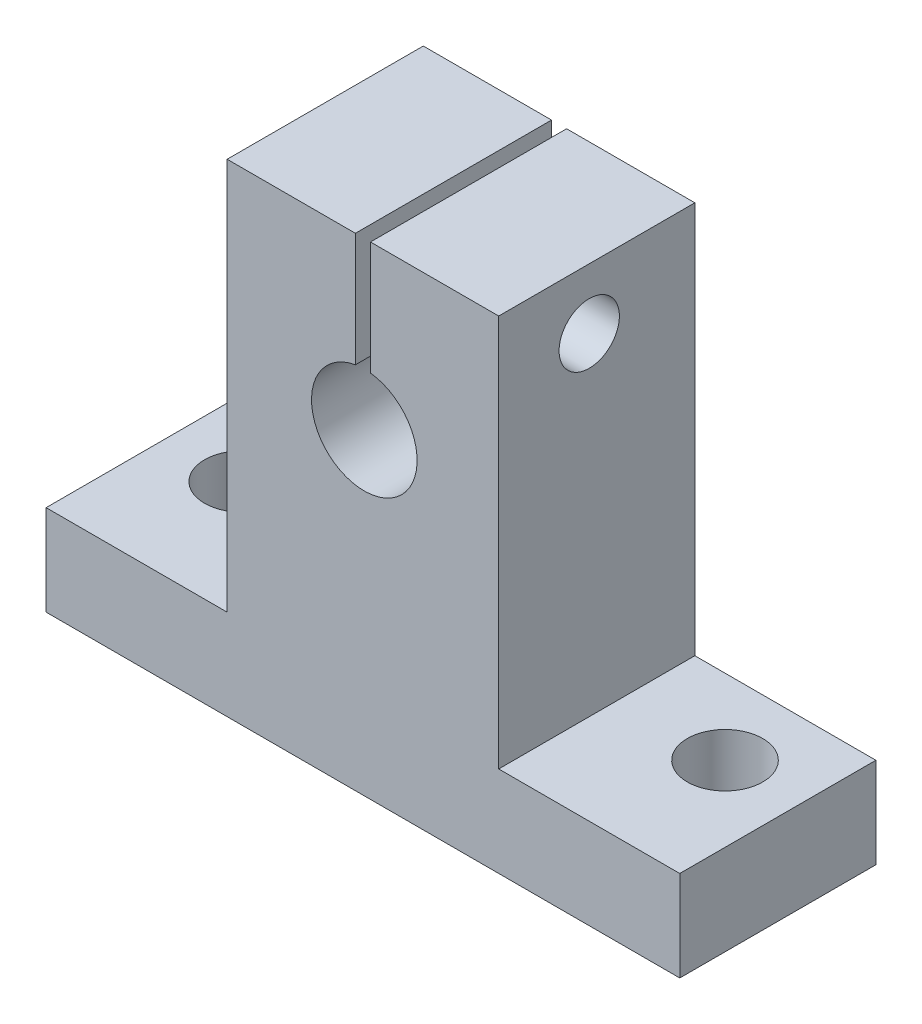
SolidWorks part; units mm, degrees
ref_plane "Front Plane" through (0, 0, 0) normal (0, 0, 1) x (1, 0, 0)
ref_plane "Top Plane" through (0, 0, 0) normal (0, 1, 0) x (1, 0, 0)
ref_plane "Right Plane" through (0, 0, 0) normal (1, 0, 0) x (0, 0, -1)
sketch "Sketch1" plane through (0, 0, 0) normal (0, 1, 0) x (1, 0, 0)
  line L1 (21, 6.5) -> (-21, 6.5)
  line L2 (21, 6.5) -> (21, -6.5)
  line L3 (21, -6.5) -> (-21, -6.5)
  line L4 (-21, 6.5) -> (-21, -6.5)
  line L5 (21, 6.5) -> (-21, -6.5) construction
  line L6 (21, -6.5) -> (-21, 6.5) construction
  circle A0 centre (-16, 1.5) radius 2.5
  circle A1 centre (16, 1.5) radius 2.5
  point P0 (0, 0)
  dimension "D4" = 5
  dimension "D8" = 5
  dimension "D1" = 13
  dimension "D2" = 42
  dimension "D3" = 5
  dimension "D5" = 5
  dimension "D6" = 5
  dimension "D7" = 5
extrude "Boss-Extrude1" add sketch "Sketch1" along normal blind 6
sketch "Sketch2" plane through (0, 6, 0) normal (0, 1, 0) x (1, 0, 0)
  line L0 (-21, -6.5) -> (21, -6.5) construction
  line L1 (-9, 6.5) -> (9, 6.5)
  line L2 (-9, 6.5) -> (-9, -6.5)
  line L3 (-9, -6.5) -> (9, -6.5)
  line L4 (9, 6.5) -> (9, -6.5)
  line L5 (-9, 6.5) -> (9, -6.5) construction
  line L6 (-9, -6.5) -> (9, 6.5) construction
  point P0 (0, 0)
  dimension "D1" = 18
extrude "Boss-Extrude2" add sketch "Sketch2" along normal blind 26
sketch "Sketch3" plane through (0, 0, 6.5) normal (0, 0, 1) x (1, 0, 0)
  line L0 (-9, 32) -> (9, 32) construction
  line L1 (-0.5, 32) -> (-0.5, 24.4496)
  line L2 (0.5, 32) -> (0.5, 24.4761)
  line L3 (-0.5, 32) -> (0.5, 32)
  circle A0 centre (0.092, 21) radius 3.5
  point P8 (0, 32)
  line M7 (9, 32) -> (-9, 32)
  dimension "D4" = 7
  dimension "D1" = 11
  dimension "D2" = 1
  dimension "D3" = 0.5
extrude "Cut-Extrude1" cut sketch "Sketch3" against normal blind 26 contours A0 | A0 L2 L1 M7
sketch "Sketch4" plane through (9, 0, 0) normal (1, 0, 0) x (0, 0, -1)
  line L0 (-6.5, 32) -> (6.5, 32) construction
  line L1 (6.5, 32) -> (6.5, 6) construction
  circle A0 centre (-0.5, 28) radius 2
  dimension "D1" = 4
  dimension "D2" = 4
  dimension "D3" = 7
extrude "Cut-Extrude2" cut sketch "Sketch4" against normal blind 26
